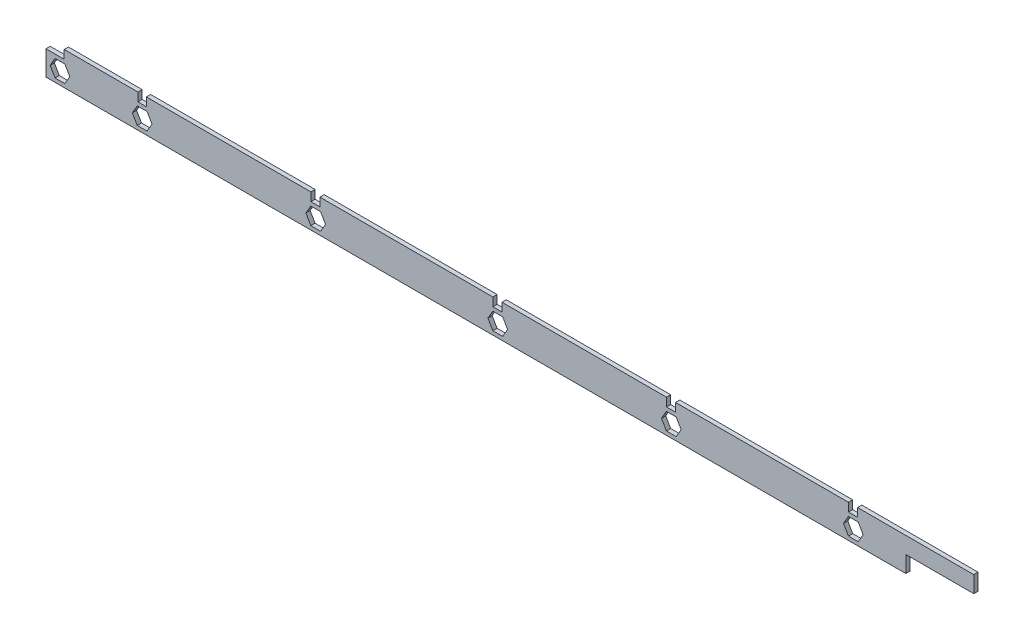
SolidWorks part; units mm, degrees
ref_plane "Front Plane" through (0, 0, 0) normal (0, 0, 1) x (1, 0, 0)
ref_plane "Top Plane" through (0, 0, 0) normal (0, 1, 0) x (1, 0, 0)
ref_plane "Right Plane" through (0, 0, 0) normal (1, 0, 0) x (0, 0, -1)
sketch "Sketch1" plane through (0, 0, 0) normal (0, 0, 1) x (1, 0, 0)
  line L0 (6453.2742, 2700.301) -> (6453.2742, 2697.126)
  line L1 (6545.4953, 2700.301) -> (6545.4953, 2697.126)
  line L2 (6548.8989, 2700.301) -> (6548.8989, 2697.126)
  line L3 (6613.5546, 2700.301) -> (6613.5546, 2697.126)
  line L4 (6616.9582, 2700.301) -> (6616.9582, 2697.126)
  line L5 (6678.4389, 2700.301) -> (6678.4389, 2697.126)
  line L6 (6681.8425, 2700.301) -> (6681.8425, 2697.126)
  line L7 (6746.4982, 2700.301) -> (6746.4982, 2697.126)
  line L8 (6749.9018, 2700.301) -> (6749.9018, 2697.126)
  line L9 (6484.2602, 2689.3536) -> (6486.0932, 2692.5286)
  line L10 (6486.0932, 2692.5286) -> (6484.2602, 2695.7036)
  line L11 (6484.2602, 2695.7036) -> (6480.594, 2695.7036)
  line L12 (6480.594, 2695.7036) -> (6478.7609, 2692.5286)
  line L13 (6478.7609, 2692.5286) -> (6480.594, 2689.3536)
  line L14 (6480.594, 2689.3536) -> (6484.2602, 2689.3536)
  line L15 (6749.9018, 2697.126) -> (6746.4982, 2697.126)
  line L16 (6681.8425, 2697.126) -> (6678.4389, 2697.126)
  line L17 (6616.9582, 2697.126) -> (6613.5546, 2697.126)
  line L18 (6548.8989, 2697.126) -> (6545.4953, 2697.126)
  line L19 (6484.0146, 2697.126) -> (6480.8396, 2697.126)
  line L20 (6453.2742, 2697.126) -> (6446.467, 2697.126)
  line L21 (6793.3421, 2700.301) -> (6749.9018, 2700.301)
  line L22 (6746.4982, 2700.301) -> (6681.8425, 2700.301)
  line L23 (6678.4389, 2700.301) -> (6616.9582, 2700.301)
  line L24 (6613.5546, 2700.301) -> (6548.8989, 2700.301)
  line L25 (6545.4953, 2700.301) -> (6484.0146, 2700.301)
  line L26 (6480.8396, 2700.301) -> (6453.2742, 2700.301)
  line L27 (6767.9421, 2687.9312) -> (6446.467, 2687.9312)
  line L28 (6484.0146, 2700.301) -> (6484.0146, 2697.126)
  line L29 (6480.8396, 2700.301) -> (6480.8396, 2697.126)
  line L30 (6549.1445, 2689.3536) -> (6550.9775, 2692.5286)
  line L31 (6550.9775, 2692.5286) -> (6549.1445, 2695.7036)
  line L32 (6549.1445, 2695.7036) -> (6545.4783, 2695.7036)
  line L33 (6545.4783, 2695.7036) -> (6543.6452, 2692.5286)
  line L34 (6543.6452, 2692.5286) -> (6545.4783, 2689.3536)
  line L35 (6545.4783, 2689.3536) -> (6549.1445, 2689.3536)
  line L36 (6617.2038, 2689.3536) -> (6619.0368, 2692.5286)
  line L37 (6619.0368, 2692.5286) -> (6617.2038, 2695.7036)
  line L38 (6617.2038, 2695.7036) -> (6613.5376, 2695.7036)
  line L39 (6613.5376, 2695.7036) -> (6611.7045, 2692.5286)
  line L40 (6611.7045, 2692.5286) -> (6613.5376, 2689.3536)
  line L41 (6613.5376, 2689.3536) -> (6617.2038, 2689.3536)
  line L42 (6682.0881, 2689.3536) -> (6683.9211, 2692.5286)
  line L43 (6683.9211, 2692.5286) -> (6682.0881, 2695.7036)
  line L44 (6682.0881, 2695.7036) -> (6678.4219, 2695.7036)
  line L45 (6678.4219, 2695.7036) -> (6676.5888, 2692.5286)
  line L46 (6676.5888, 2692.5286) -> (6678.4219, 2689.3536)
  line L47 (6678.4219, 2689.3536) -> (6682.0881, 2689.3536)
  line L48 (6750.1474, 2689.3536) -> (6751.9804, 2692.5286)
  line L49 (6751.9804, 2692.5286) -> (6750.1474, 2695.7036)
  line L50 (6750.1474, 2695.7036) -> (6746.4812, 2695.7036)
  line L51 (6746.4812, 2695.7036) -> (6744.6481, 2692.5286)
  line L52 (6744.6481, 2692.5286) -> (6746.4812, 2689.3536)
  line L53 (6746.4812, 2689.3536) -> (6750.1474, 2689.3536)
  line L54 (6453.5198, 2689.3536) -> (6455.3529, 2692.5286)
  line L55 (6455.3529, 2692.5286) -> (6453.5198, 2695.7036)
  line L56 (6453.5198, 2695.7036) -> (6449.8536, 2695.7036)
  line L57 (6449.8536, 2695.7036) -> (6448.0205, 2692.5286)
  line L58 (6448.0205, 2692.5286) -> (6449.8536, 2689.3536)
  line L59 (6449.8536, 2689.3536) -> (6453.5198, 2689.3536)
  line L60 (6446.467, 2687.9312) -> (6446.467, 2697.126)
  line L61 (6767.9421, 2694.1161) -> (6767.9421, 2687.9312)
  line L62 (6793.3421, 2700.301) -> (6793.3421, 2694.1161)
  line L63 (6767.9421, 2694.1161) -> (6793.3421, 2694.1161)
extrude "Boss-Extrude1" add sketch "Sketch1" along normal blind 1.5875
